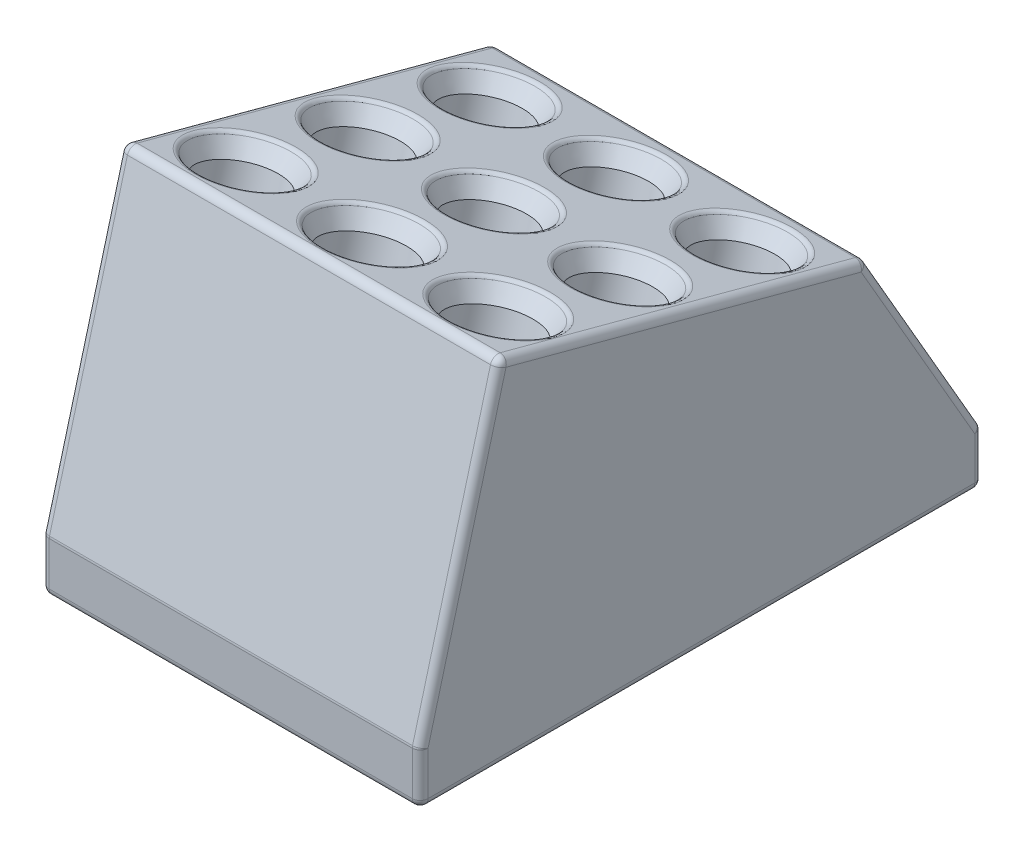
SolidWorks part; units mm, degrees
ref_plane "Front Plane" through (0, 0, 0) normal (0, 0, 1) x (1, 0, 0)
ref_plane "Top Plane" through (0, 0, 0) normal (0, 1, 0) x (1, 0, 0)
ref_plane "Right Plane" through (0, 0, 0) normal (1, 0, 0) x (0, 0, -1)
sketch "Sketch1" plane through (0, 0, 0) normal (1, 0, 0) x (0, 0, -1)
  line L0 (0, 0) -> (0, 10)
  line L1 (0, 10) -> (15.2547, 66.9313)
  line L2 (15.2547, 66.9313) -> (84.8013, 48.2963)
  line L3 (84.8013, 48.2963) -> (106.9117, 10)
  line L4 (106.9117, 10) -> (106.9117, 0)
  line L5 (106.9117, 0) -> (0, 0)
  line L6 (84.8013, 48.2963) -> (71.8604, 0) construction
  dimension "D1" = 72
  dimension "D2" = 10
  dimension "D3" = 15
  dimension "D4" = 30
  dimension "D6" = 50
extrude "Boss-Extrude1" add sketch "Sketch1" along normal blind 72
sketch "Sketch3" plane through (0, 66.2614, -17.7547) normal (0, 0.9659, -0.2588) x (1, 0, 0)
  line L0 (72, -2.5882) -> (0, -2.5882) construction
  line L1 (0, 69.4118) -> (0, -2.5882) construction
  line L2 (12, 9.4118) -> (12, 89.3531) construction
  line L3 (12, 9.4118) -> (90.0747, 9.4118) construction
  point P0 (12, 9.4118)
  point P11 (36, 9.4118)
  point P12 (60, 9.4118)
  point P13 (36, 33.4118)
  point P14 (60, 33.4118)
  point P15 (36, 57.4118)
  point P16 (60, 57.4118)
  point P17 (12, 33.4118)
  point P18 (12, 57.4118)
  dimension "D1" = 12
  dimension "D2" = 12
  dimension "D3" = 3
  dimension "D4" = 3
sketch "Sketch4" plane through (0, 66.2614, -17.7547) normal (0, 0.9659, -0.2588) x (1, 0, 0)
  circle A0 centre (60, 9.4118) radius 7.75
  circle A1 centre (36, 9.4118) radius 7.75
  circle A2 centre (12, 9.4118) radius 7.35
  circle A3 centre (60, 33.4118) radius 7.35
  circle A4 centre (36, 33.4118) radius 7.35
  circle A5 centre (12, 33.4118) radius 7.35
  circle A6 centre (60, 57.4118) radius 7.35
  circle A7 centre (36, 57.4118) radius 7.35
  circle A8 centre (12, 57.4118) radius 7.35
  point P26 (0, 0)
  dimension "D1" = 15.5
  dimension "D3" = 14.7
extrude "Cut-Extrude1" cut sketch "Sketch4" against normal blind 45
chamfer "Chamfer1" distance 2 angle 60 9 edges at (12, 53.3044, -66.1107) (36, 53.3044, -66.1107) (60, 53.3044, -66.1107) (60, 59.5161, -42.9285) (36, 59.5161, -42.9285) (12, 59.5161, -42.9285) (12, 65.7278, -19.7462) (36, 65.8313, -19.3599) (60, 65.8313, -19.3599)
fillet "Fillet1" radius 1.5 9 edges at (12, 9.8378, -54.4638) (36, 9.8378, -54.4638) (60, 9.8378, -54.4638) (12, 16.0494, -31.2816) (36, 16.0494, -31.2816) (60, 16.0494, -31.2816) (12, 22.2611, -8.0994) (36, 22.3646, -7.713) (60, 22.3646, -7.713)
fillet "Fillet2" radius 1.5 18 edges at (0, 5, 0) (72, 5, 0) (72, 38.4656, -7.6273) (36, 10, 0) (36, 0, 0) (72, 0, -53.4559) (36, 0, -106.9117) (72, 5, -106.9117) (72, 29.1481, -95.8565) (72, 57.6138, -50.028) (0, 38.4656, -7.6273) (36, 66.9313, -15.2547) (36, 10, -106.9117) (0, 5, -106.9117) (0, 0, -53.4559) (36, 48.2963, -84.8013) (0, 57.6138, -50.028) (0, 29.1481, -95.8565)
fillet "Fillet3" radius 1 9 edges at (12, 48.9822, -82.2416) (36, 48.9822, -82.2416) (60, 48.9822, -82.2416) (60, 55.1938, -59.0594) (36, 55.1938, -59.0594) (12, 55.1938, -59.0594) (12, 61.4055, -35.8772) (36, 61.3019, -36.2636) (60, 61.3019, -36.2636)
